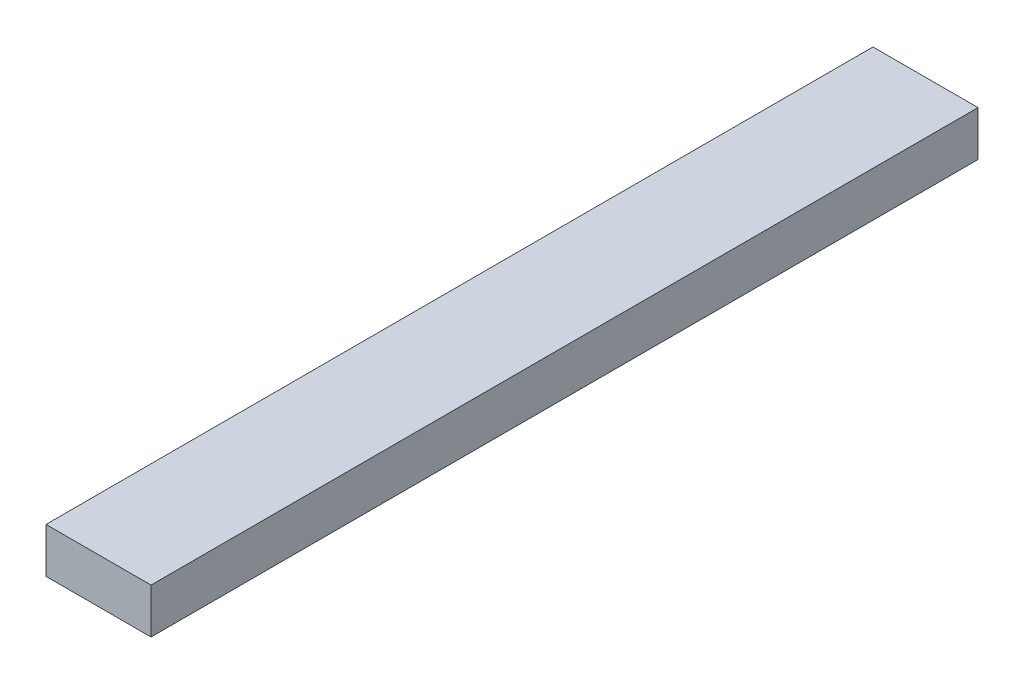
SolidWorks part; units mm, degrees
material "Pine"
ref_plane "Front Plane" through (0, 0, 0) normal (0, 0, 1) x (1, 0, 0)
ref_plane "Top Plane" through (0, 0, 0) normal (0, 1, 0) x (1, 0, 0)
ref_plane "Right Plane" through (0, 0, 0) normal (1, 0, 0) x (0, 0, -1)
sketch "Sketch1" plane through (0, 0, 0) normal (0, 0, 1) x (1, 0, 0)
  line L1 (-44.45, -19.05) -> (44.45, -19.05)
  line L2 (-44.45, -19.05) -> (-44.45, 19.05)
  line L3 (-44.45, 19.05) -> (44.45, 19.05)
  line L4 (44.45, -19.05) -> (44.45, 19.05)
  line L5 (-44.45, -19.05) -> (44.45, 19.05) construction
  line L6 (-44.45, 19.05) -> (44.45, -19.05) construction
  point P0 (0, 0)
  dimension "D1" = 38.1
  dimension "D2" = 88.9
extrude "Boss-Extrude1" add sketch "Sketch1" along normal blind 700
